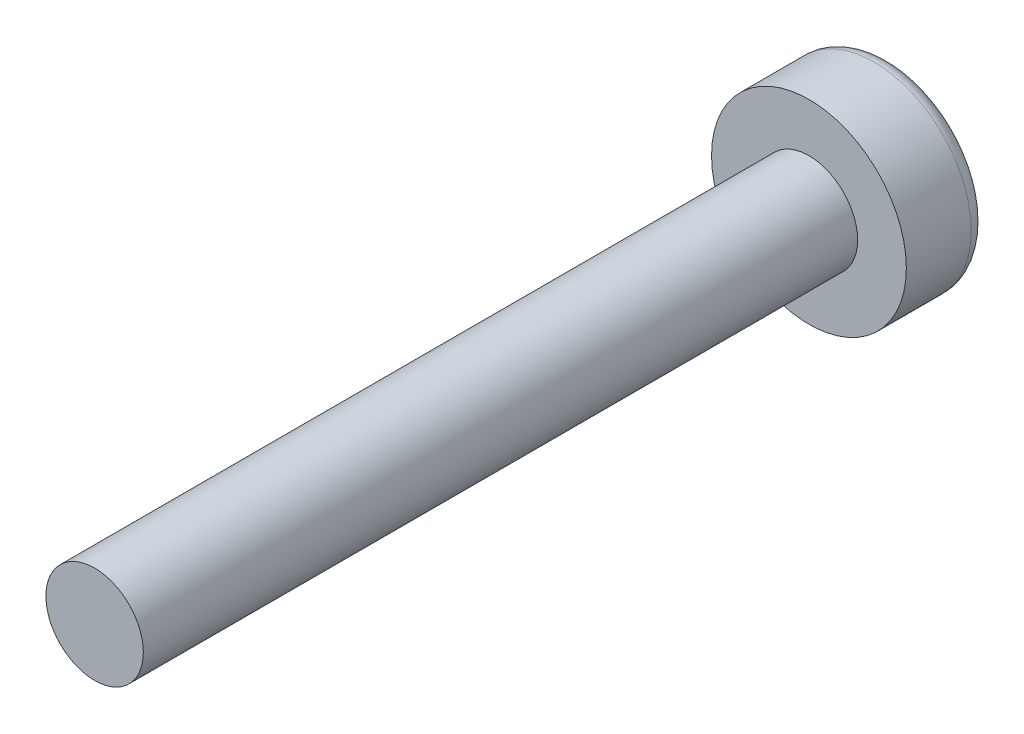
SolidWorks part; units mm, degrees
ref_plane "Plan1" through (0, 0, 0) normal (0, 0, 1) x (1, 0, 0)
ref_plane "Plan2" through (0, 0, 0) normal (0, 1, 0) x (1, 0, 0)
ref_plane "Plan3" through (0, 0, 0) normal (1, 0, 0) x (0, 0, -1)
sketch "Esquisse1" plane through (0, 0, 0) normal (0, 0, 1) x (1, 0, 0)
  circle A0 centre (0, 0) radius 3
extrude "Base-Extrusion" add sketch "Esquisse1" along normal blind 2.5
sketch "Esquisse2" plane through (0, 0, 2.5) normal (0, 0, 1) x (1, 0, 0)
  circle A0 centre (0, 0) radius 1.5
extrude "Boss.-Extru.1" add sketch "Esquisse2" along normal blind 22
fillet "Congé1" radius 0.5
sketch "Esquisse3" plane through (0, 0, 0) normal (0, 0, -1) x (-1, 0, 0)
  line L1 (1.7321, 0) -> (0.866, 1.5)
  line L2 (0.866, 1.5) -> (-0.866, 1.5)
  line L3 (-0.866, 1.5) -> (-1.7321, 0)
  line L4 (-1.7321, 0) -> (-0.866, -1.5)
  line L5 (-0.866, -1.5) -> (0.866, -1.5)
  line L6 (0.866, -1.5) -> (1.7321, 0)
  circle A0 centre (0, 0) radius 1.5 construction
extrude "Enlèv. mat.-Extru.1" cut sketch "Esquisse3" against normal blind 2
